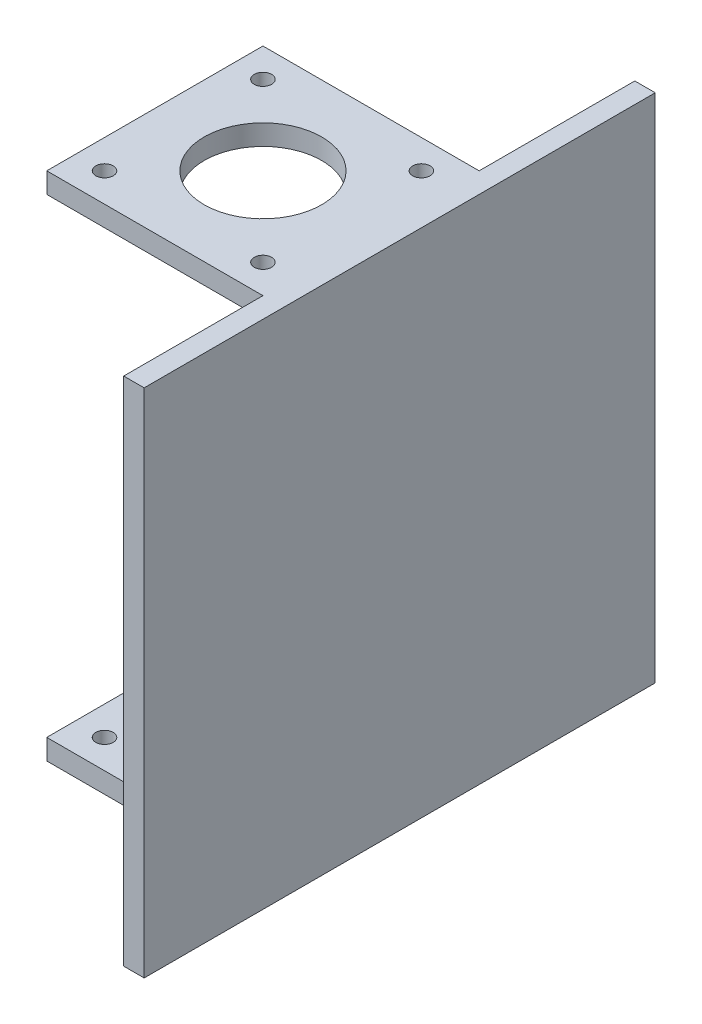
SolidWorks part; units mm, degrees
ref_plane "Front Plane" through (0, 0, 0) normal (0, 0, 1) x (1, 0, 0)
ref_plane "Top Plane" through (0, 0, 0) normal (0, 1, 0) x (1, 0, 0)
ref_plane "Right Plane" through (0, 0, 0) normal (1, 0, 0) x (0, 0, -1)
sketch "Sketch2" plane through (0, 0, 0) normal (0, 1, 0) x (1, 0, 0)
  line L1 (-21.15, -21.15) -> (21.15, -21.15)
  line L2 (-21.15, -21.15) -> (-21.15, 21.15)
  line L3 (-21.15, 21.15) -> (21.15, 21.15)
  line L4 (21.15, -21.15) -> (21.15, 21.15)
  line L5 (-21.15, -21.15) -> (21.15, 21.15) construction
  line L6 (-21.15, 21.15) -> (21.15, -21.15) construction
  circle A0 centre (-15.5, 15.5) radius 1.7
  circle A1 centre (15.5, 15.5) radius 1.7
  circle A2 centre (15.5, -15.5) radius 1.7
  circle A3 centre (-15.5, -15.5) radius 1.7
  circle A4 centre (0, 0) radius 11.5
  point P0 (0, 0)
  dimension "D4" = 3.4
  dimension "D5" = 23
  dimension "D1" = 42.3
  dimension "D2" = 42.3
  dimension "D3" = 31
extrude "Boss-Extrude1" add sketch "Sketch2" along normal blind 4
ref_plane "Plane1" through (-21.15, 0, -21.15) normal (-1, 0, 0) x (0, 0, 1)
sketch "Sketch6" plane through (0, 0, -21.15) normal (0, 0, -1) x (-1, 0, 0)
  line L0 (0, 0) -> (28.2537, 0) construction
ref_plane "Plane3" through (-21.15, 4, -21.15) normal (-1, 0, 0) x (0, 0, 1)
ref_plane "Plane4" through (-21.15, 4, -21.15) normal (0, 0, 1) x (1, 0, 0)
ref_plane "Plane5" through (21.15, 4, 21.15) normal (1, 0, 0) x (0, 0, -1)
sketch "Sketch10" plane through (21.15, 4, 21.15) normal (1, 0, 0) x (0, 0, -1)
  line L0 (0, 0) -> (-9.5873, 0) construction
  line L1 (-27.2441, 0) -> (72.7559, 0)
  line L2 (72.7559, 0) -> (72.7559, -100)
  line L3 (-27.2441, 0) -> (-27.2441, -100)
  line L4 (-27.2441, -100) -> (72.7559, -100)
  dimension "D1" = 100
  dimension "D2" = 100
extrude "Boss-Extrude3" add sketch "Sketch10" along normal blind 4
ref_plane "Plane6" through (0, -46, 0) normal (0, -1, 0) x (-1, 0, 0)
mirror "Mirror1" about plane through (0, -46, 0) normal (0, -1, 0) of "Boss-Extrude1"
